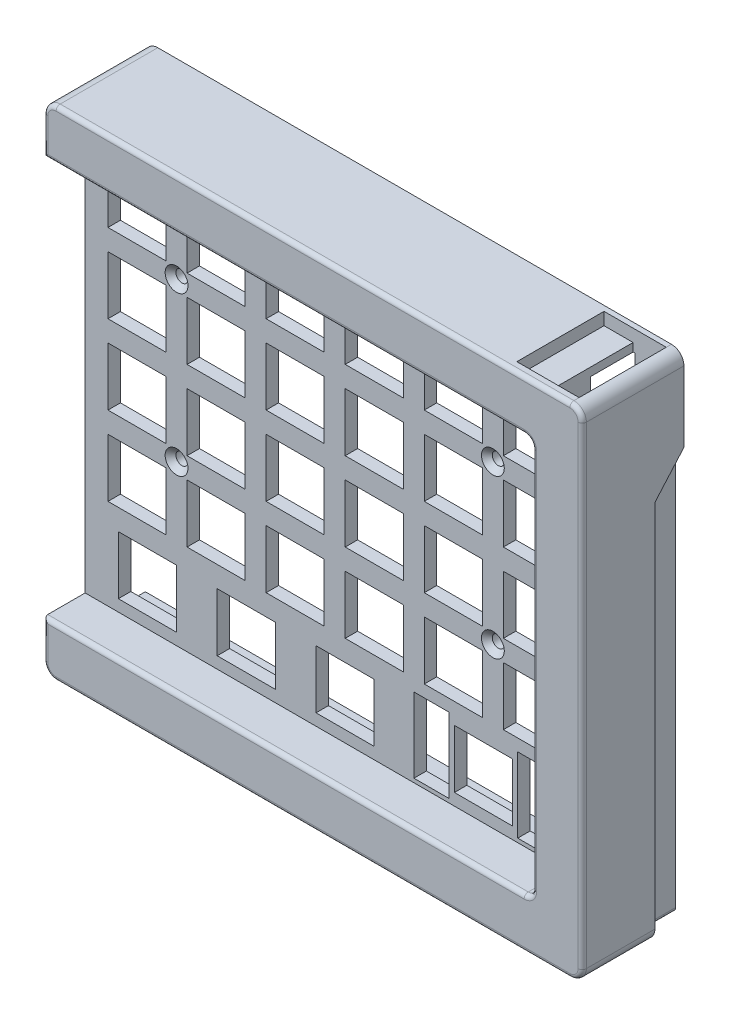
SolidWorks part; units mm, degrees
ref_plane "Front Plane" through (0, 0, 0) normal (0, 0, 1) x (1, 0, 0)
ref_plane "Top Plane" through (0, 0, 0) normal (0, 1, 0) x (1, 0, 0)
ref_plane "Right Plane" through (0, 0, 0) normal (1, 0, 0) x (0, 0, -1)
sketch "Sketch1" plane through (0, 0, 0) normal (0, 0, 1) x (1, 0, 0)
  line L1 (-61.875, -60) -> (61.875, -60)
  line L2 (-64.875, -57) -> (-64.875, 57)
  line L3 (-61.875, 60) -> (61.875, 60)
  line L4 (64.875, -57) -> (64.875, 57)
  line L5 (-64.875, -60) -> (64.875, 60) construction
  line L6 (-64.875, 60) -> (64.875, -60) construction
  arc A0 (61.875, -60) -> (64.875, -57) centre (61.875, -57) ccw
  arc A1 (61.875, 60) -> (64.875, 57) centre (61.875, 57) cw
  arc A2 (-64.875, 57) -> (-61.875, 60) centre (-61.875, 57) cw
  arc A3 (-61.875, -60) -> (-64.875, -57) centre (-61.875, -57) cw
  point P0 (0, 0)
  dimension "D3" = 3
  dimension "D1" = 129.75
  dimension "D2" = 120
extrude "Main Extrusion" add sketch "Sketch1" along normal blind 24.5
sketch "Sketch3" plane through (0, 0, 24.5) normal (0, 0, 1) x (1, 0, 0)
  line L0 (-64.875, 57) -> (-64.875, -57) construction
  line L1 (-64.875, 48) -> (50.875, 48)
  line L2 (-64.875, 48) -> (-64.875, -48)
  line L3 (-64.875, -48) -> (50.875, -48)
  line L4 (52.875, 46) -> (52.875, -46)
  line L5 (-64.875, 48) -> (52.875, -48) construction
  line L6 (-64.875, -48) -> (52.875, 48) construction
  line L7 (-61.875, -60) -> (61.875, -60) construction
  line L9 (61.875, 60) -> (-61.875, 60) construction
  line L11 (64.875, -57) -> (64.875, 57) construction
  arc A0 (50.875, 48) -> (52.875, 46) centre (50.875, 46) cw
  arc A1 (50.875, -48) -> (52.875, -46) centre (50.875, -46) ccw
  point P0 (-6, 0)
  dimension "D5" = 2
  dimension "D1" = 0
  dimension "D2" = 12
  dimension "D3" = 12
  dimension "D4" = 12
extrude "Front Cave" cut sketch "Sketch3" against normal blind 10
sketch "Sketch2" plane through (0, 0, 14.5) normal (0, 0, 1) x (1, 0, 0)
  line L0 (-59.375, -7.1) -> (-59.375, 6.9)
  line L1 (-59.375, 31) -> (-45.375, 31)
  line L2 (-59.375, 31) -> (-59.375, 45)
  line L3 (-59.375, 45) -> (-45.375, 45)
  line L4 (-45.375, 31) -> (-45.375, 45)
  line L5 (-59.375, 31) -> (-45.375, 45) construction
  line L6 (-59.375, 45) -> (-45.375, 31) construction
  line L7 (-40.325, 31) -> (-40.325, 45)
  line L8 (-40.325, 31) -> (-26.325, 31)
  line L9 (-26.325, 31) -> (-26.325, 45)
  line L10 (-40.325, 45) -> (-26.325, 45)
  line L11 (-21.275, 31) -> (-21.275, 45)
  line L12 (-21.275, 31) -> (-7.275, 31)
  line L13 (-7.275, 31) -> (-7.275, 45)
  line L14 (-21.275, 45) -> (-7.275, 45)
  line L15 (-2.225, 31) -> (-2.225, 45)
  line L16 (-2.225, 31) -> (11.775, 31)
  line L17 (11.775, 31) -> (11.775, 45)
  line L18 (-2.225, 45) -> (11.775, 45)
  line L19 (16.825, 31) -> (16.825, 45)
  line L20 (16.825, 31) -> (30.825, 31)
  line L21 (30.825, 31) -> (30.825, 45)
  line L22 (16.825, 45) -> (30.825, 45)
  line L23 (35.875, 31) -> (35.875, 45)
  line L24 (35.875, 31) -> (49.875, 31)
  line L25 (49.875, 31) -> (49.875, 45)
  line L26 (35.875, 45) -> (49.875, 45)
  line L27 (31.084, -31.15) -> (31.084, -45.15) construction
  line L28 (22.8344, -29.05) -> (14.3344, -29.05)
  line L29 (-59.375, 6.9) -> (-45.375, 6.9)
  line L30 (-59.375, 11.95) -> (-59.375, 25.95)
  line L31 (-59.375, 11.95) -> (-45.375, 11.95)
  line L32 (-45.375, 11.95) -> (-45.375, 25.95)
  line L33 (-59.375, 25.95) -> (-45.375, 25.95)
  line L34 (-40.325, 11.95) -> (-40.325, 25.95)
  line L35 (-40.325, 25.95) -> (-26.325, 25.95)
  line L36 (-26.325, 11.95) -> (-26.325, 25.95)
  line L37 (-40.325, 11.95) -> (-26.325, 11.95)
  line L38 (-21.275, 11.95) -> (-21.275, 25.95)
  line L39 (-21.275, 25.95) -> (-7.275, 25.95)
  line L40 (-7.275, 11.95) -> (-7.275, 25.95)
  line L41 (-21.275, 11.95) -> (-7.275, 11.95)
  line L42 (-2.225, 11.95) -> (-2.225, 25.95)
  line L43 (-2.225, 25.95) -> (11.775, 25.95)
  line L44 (11.775, 11.95) -> (11.775, 25.95)
  line L45 (-2.225, 11.95) -> (11.775, 11.95)
  line L46 (16.825, 11.95) -> (16.825, 25.95)
  line L47 (16.825, 25.95) -> (30.825, 25.95)
  line L48 (30.825, 11.95) -> (30.825, 25.95)
  line L49 (16.825, 11.95) -> (30.825, 11.95)
  line L50 (35.875, 11.95) -> (35.875, 25.95)
  line L51 (35.875, 25.95) -> (49.875, 25.95)
  line L52 (49.875, 11.95) -> (49.875, 25.95)
  line L53 (35.875, 11.95) -> (49.875, 11.95)
  line L54 (-45.375, -7.1) -> (-45.375, 6.9)
  line L55 (-59.375, -7.1) -> (-45.375, -7.1)
  line L56 (-40.325, -7.1) -> (-40.325, 6.9)
  line L57 (-40.325, 6.9) -> (-26.325, 6.9)
  line L58 (-26.325, -7.1) -> (-26.325, 6.9)
  line L59 (-40.325, -7.1) -> (-26.325, -7.1)
  line L60 (-21.275, -7.1) -> (-21.275, 6.9)
  line L61 (-21.275, 6.9) -> (-7.275, 6.9)
  line L62 (-7.275, -7.1) -> (-7.275, 6.9)
  line L63 (-21.275, -7.1) -> (-7.275, -7.1)
  line L64 (-2.225, -7.1) -> (-2.225, 6.9)
  line L65 (-2.225, 6.9) -> (11.775, 6.9)
  line L66 (11.775, -7.1) -> (11.775, 6.9)
  line L67 (-2.225, -7.1) -> (11.775, -7.1)
  line L68 (16.825, -7.1) -> (16.825, 6.9)
  line L69 (16.825, 6.9) -> (30.825, 6.9)
  line L70 (30.825, -7.1) -> (30.825, 6.9)
  line L71 (16.825, -7.1) -> (30.825, -7.1)
  line L72 (35.875, -7.1) -> (35.875, 6.9)
  line L73 (35.875, 6.9) -> (49.875, 6.9)
  line L74 (49.875, -7.1) -> (49.875, 6.9)
  line L75 (35.875, -7.1) -> (49.875, -7.1)
  line L76 (-59.375, -26.15) -> (-59.375, -12.15)
  line L77 (-59.375, -12.15) -> (-45.375, -12.15)
  line L78 (-45.375, -26.15) -> (-45.375, -12.15)
  line L79 (-59.375, -26.15) -> (-45.375, -26.15)
  line L80 (-40.325, -26.15) -> (-40.325, -12.15)
  line L81 (-40.325, -12.15) -> (-26.325, -12.15)
  line L82 (-26.325, -26.15) -> (-26.325, -12.15)
  line L83 (-40.325, -26.15) -> (-26.325, -26.15)
  line L84 (-21.275, -26.15) -> (-21.275, -12.15)
  line L85 (-21.275, -12.15) -> (-7.275, -12.15)
  line L86 (-7.275, -26.15) -> (-7.275, -12.15)
  line L87 (-21.275, -26.15) -> (-7.275, -26.15)
  line L88 (-2.225, -26.15) -> (-2.225, -12.15)
  line L89 (-2.225, -12.15) -> (11.775, -12.15)
  line L90 (11.775, -26.15) -> (11.775, -12.15)
  line L91 (-2.225, -26.15) -> (11.775, -26.15)
  line L92 (16.825, -26.15) -> (16.825, -12.15)
  line L93 (16.825, -12.15) -> (30.825, -12.15)
  line L94 (30.825, -26.15) -> (30.825, -12.15)
  line L95 (16.825, -26.15) -> (30.825, -26.15)
  line L96 (35.875, -26.15) -> (35.875, -12.15)
  line L97 (35.875, -12.15) -> (49.875, -12.15)
  line L98 (49.875, -26.15) -> (49.875, -12.15)
  line L99 (35.875, -26.15) -> (49.875, -26.15)
  line L100 (-33.063, -31.2) -> (-33.063, -45.2)
  line L101 (-56.875, -31.2) -> (-42.875, -31.2)
  line L102 (-56.875, -31.2) -> (-56.875, -45.2)
  line L103 (-56.875, -45.2) -> (-42.875, -45.2)
  line L104 (-42.875, -31.2) -> (-42.875, -45.2)
  line L105 (-56.875, -31.2) -> (-42.875, -45.2) construction
  line L106 (-56.875, -45.2) -> (-42.875, -31.2) construction
  line L107 (-33.063, -31.2) -> (-19.063, -31.2)
  line L108 (-19.063, -31.2) -> (-19.063, -45.2)
  line L109 (-33.063, -45.2) -> (-19.063, -45.2)
  line L110 (-9.251, -31.2) -> (-9.251, -45.2)
  line L111 (-9.251, -31.2) -> (4.749, -31.2)
  line L112 (4.749, -31.2) -> (4.749, -45.2)
  line L113 (-9.251, -45.2) -> (4.749, -45.2)
  line L114 (-61.875, -60) -> (61.875, -60) construction
  line L115 (24.084, -31.15) -> (38.084, -31.15)
  line L116 (24.084, -31.15) -> (24.084, -45.15)
  line L117 (24.084, -45.15) -> (38.084, -45.15)
  line L118 (38.084, -31.15) -> (38.084, -45.15)
  line L119 (24.084, -31.15) -> (38.084, -45.15) construction
  line L120 (24.084, -45.15) -> (38.084, -31.15) construction
  line L125 (61.875, 60) -> (-61.875, 60) construction
  line L126 (-64.875, 57) -> (-64.875, 48) construction
  line L127 (14.3344, -47.05) -> (14.3344, -29.05)
  line L132 (22.8344, -47.05) -> (14.3344, -47.05)
  line L133 (22.8344, -47.05) -> (22.8344, -29.05)
  line L134 (39.3336, -47.05) -> (47.8336, -47.05)
  line L135 (39.3336, -47.05) -> (39.3336, -29.05)
  line L136 (39.3336, -29.05) -> (47.8336, -29.05)
  line L137 (47.8336, -47.05) -> (47.8336, -29.05)
  line L138 (39.3336, -47.05) -> (47.8336, -29.05) construction
  line L139 (39.3336, -29.05) -> (47.8336, -47.05) construction
  point P0 (-52.375, 38)
  point P29 (-49.875, -38.2)
  point P107 (31.084, -38.15)
  point P136 (18.584, -37.55)
  point P141 (43.5836, -38.05)
  dimension "D1" = 14
  dimension "D2" = 14
  dimension "D3" = 6
  dimension "D5" = 15
  dimension "D6" = 5.05
  dimension "D7" = 2
  dimension "D8" = 5.05
  dimension "D10" = 5.05
  dimension "D11" = 14
  dimension "D12" = 14
  dimension "D13" = 5.5
  dimension "D14" = 5.05
  dimension "D16" = 9.812
  dimension "D17" = 14
  dimension "D18" = 14
  dimension "D19" = 19.335
  dimension "D20" = 5
  dimension "D21" = 8
  dimension "D44" = 8.5
  dimension "D45" = 18
  dimension "D46" = 12.5
  dimension "D47" = 12.95
  dimension "D9" = 3
  dimension "D15" = 3
extrude "Key Cutouts" cut sketch "Sketch2" against normal blind 3
sketch "Sketch4" plane through (0, 0, 0) normal (0, 0, 1) x (1, 0, 0)
  line L0 (61.875, 60) -> (-61.875, 60) construction
  line L1 (-64.875, 55) -> (54.375, 55)
  line L2 (-64.875, 55) -> (-64.875, -55)
  line L3 (-64.875, -55) -> (59.875, -55)
  line L4 (59.875, 17.5) -> (59.875, -55)
  line L5 (-64.875, 55) -> (59.875, -55) construction
  line L7 (-61.875, -60) -> (61.875, -60) construction
  line L8 (64.875, -57) -> (64.875, 57) construction
  line L12 (59.875, 17.5) -> (54.375, 17.5)
  line L13 (54.375, 55) -> (54.375, 17.5)
  line L14 (-64.875, 57) -> (-64.875, -57) construction
  point P0 (0.3939, -2.5517)
  dimension "D1" = 5
  dimension "D2" = 5
  dimension "D3" = 5
  dimension "D4" = 5.5
  dimension "D5" = 37.5
extrude "Cut-Extrude1" cut sketch "Sketch4" along normal up to surface (11.5 mm away) contours L2 L3 L4 L12 L13 L1 up to face at (-52.375, 18.95, 11.5)
hole_wizard "CSK for M2.5 Countersunk Flat Head Screw1" positions "3DSketch1" profile "Sketch5" countersink size "M2.5" standard "ISO" end condition through all
sketch3d "3DSketch1"
  line L0 (-45.375, -7.1, 14.5) -> (-45.375, 6.9, 14.5) construction
  line L1 (-26.325, -12.15, 14.5) -> (-40.325, -12.15, 14.5) construction
  line L2 (-59.375, 31, 14.5) -> (-45.375, 31, 14.5) construction
  line L4 (-40.325, 25.95, 14.5) -> (-40.325, 11.95, 14.5) construction
  line L5 (30.825, 11.95, 14.5) -> (30.825, 25.95, 14.5) construction
  line L6 (49.875, 25.95, 14.5) -> (35.875, 25.95, 14.5) construction
  line L7 (35.875, -12.15, 14.5) -> (35.875, -26.15, 14.5) construction
  line L8 (35.875, -7.1, 14.5) -> (49.875, -7.1, 14.5) construction
  point P0 (-42.85, 28.475, 14.5)
  point P2 (33.35, 28.475, 14.5)
  point P4 (33.35, -9.625, 14.5)
  point P6 (-42.85, -9.625, 14.5)
  dimension "D1" = 2.525
  dimension "D2" = 2.525
  dimension "D3" = 2.525
  dimension "D4" = 2.525
  dimension "D5" = 2.525
  dimension "D6" = 2.525
  dimension "D7" = 2.525
  dimension "D8" = 2.525
sketch "Sketch5" plane through (-42.85, 28.475, 14.5) normal (1, 0, 0) x (0, -1, 0)
  line L0 (0, 0) -> (0, 14.5)
  line L1 (0, 14.5) -> (1.45, 14.5)
  line L2 (1.45, 14.5) -> (1.45, 1.3)
  line L3 (1.45, 1.3) -> (2.75, 0)
  line L5 (2.75, 0) -> (0, 0)
  line L6 (-1.45, 1.3) -> (-2.75, 0) construction
  line L11 (0, -6.35) -> (0, 107.95) construction
  dimension "Thru Hole Dia." = 2.9
  dimension "Thru Hole Depth" = 14.5
  dimension "Near C'Sink Dia." = 5.5
  dimension "Near C'Sink Angle" = 90
sketch "Sketch6" plane through (0, -60, 0) normal (0, -1, 0) x (1, 0, 0)
  line L0 (-44.875, 0) -> (-36.875, 7)
  line L1 (-61.875, 0) -> (61.875, 0) construction
  line L2 (-36.875, 7) -> (64.875, 7)
  line L3 (64.875, 7) -> (64.875, 0)
  line L4 (64.875, 0) -> (-44.875, 0)
  line L5 (-61.875, 24.5) -> (-61.875, 0) construction
  line L7 (64.875, 24.5) -> (64.875, 0) construction
  dimension "D1" = 25
  dimension "D2" = 17
  dimension "D5" = 7
extrude "Cut-Extrude2" cut sketch "Sketch6" against normal blind 2
sketch "Sketch8" plane through (64.875, 0, 0) normal (1, 0, 0) x (0, 0, -1)
  line L0 (0, -60) -> (-7, -60)
  line L1 (0, -57) -> (0, 57) construction
  line L2 (-7, -60) -> (-7, 32)
  line L3 (-7, 32) -> (0, 40)
  line L4 (0, 40) -> (0, -60)
  line L6 (-24.5, -60) -> (-7, -60) construction
  line L7 (-24.5, 57) -> (0, 57) construction
  dimension "D3" = 17
  dimension "D4" = 25
  dimension "D5" = 7
extrude "Cut-Extrude3" cut sketch "Sketch8" against normal blind 2
fillet "Fillet1" radius 1 15 edges at (-64.875, 52.5, 24.5) (-63.9963, 59.1213, 24.5) (0, 60, 24.5) (63.9963, 59.1213, 24.5) (64.875, 0, 24.5) (63.9963, -59.1213, 24.5) (0, -60, 24.5) (-63.9963, -59.1213, 24.5) (-64.875, -52.5, 24.5) (-7, -48, 24.5) (52.2892, -47.4142, 24.5) (52.875, 0, 24.5) (52.2892, 47.4142, 24.5) (-7, 48, 24.5) (62.875, -58, 3.5)
sketch "Sketch9" plane through (0, 60, 0) normal (0, 1, 0) x (1, 0, 0)
  line L0 (61.875, -23.5) -> (61.875, 0) construction
  line L1 (61.875, -1.25) -> (53.875, -1.25)
  line L2 (61.875, -1.25) -> (61.875, -22.25)
  line L3 (61.875, -22.25) -> (53.875, -22.25)
  line L4 (53.875, -1.25) -> (53.875, -22.25)
  line L5 (-61.875, -11.75) -> (61.875, -11.75) construction
  line L6 (-61.875, -23.5) -> (-61.875, 0) construction
  point P10 (53.875, -11.75)
  dimension "D1" = 8
  dimension "D2" = 21
extrude "Cut-Extrude4" cut sketch "Sketch9" against normal blind 41
sketch "Sketch10" plane through (0, 0, 11.5) normal (0, 0, -1) x (-1, 0, 0)
  line L0 (-59.875, 17.5) -> (-54.375, 17.5) construction
  line L1 (-59.875, 17.5) -> (-53.875, 17.5)
  line L2 (-59.875, 17.5) -> (-59.875, 7.5)
  line L3 (-59.875, 7.5) -> (-53.875, 7.5)
  line L4 (-53.875, 17.5) -> (-53.875, 7.5)
  line L5 (-53.875, 55) -> (-53.875, 19) construction
  line L6 (-59.875, 17.5) -> (-59.875, -55) construction
  dimension "D1" = 10
extrude "Cut-Extrude5" cut sketch "Sketch10" against normal up to surface (10.75 mm away) up to face at (57.875, 39.5, 22.25)
sketch "Sketch11" plane through (0, 19, 0) normal (0, 1, 0) x (1, 0, 0)
  line L0 (57.875, -6.25) -> (57.875, -17.25) construction
  line L1 (59.875, -6.25) -> (59.875, -17.25)
  line L2 (55.875, -6.25) -> (55.875, -17.25)
  line L3 (53.875, -1.25) -> (53.875, -22.25) construction
  line L6 (61.875, -1.25) -> (53.875, -1.25) construction
  arc A0 (59.875, -6.25) -> (55.875, -6.25) centre (57.875, -6.25) ccw
  arc A1 (55.875, -17.25) -> (59.875, -17.25) centre (57.875, -17.25) ccw
  point P2 (57.875, -11.75)
  dimension "D1" = 2
  dimension "D2" = 11
  dimension "D3" = 4
  dimension "D4" = 10.5
extrude "Cut-Extrude6" cut sketch "Sketch11" against normal up to surface (1.5 mm away) up to face at (56.0417, 17.5, 11.25)
sketch "Sketch13" plane through (0, 0, 11.5) normal (0, 0, -1) x (-1, 0, 0)
  line L0 (-59.875, 7.5) -> (-59.875, -55) construction
  line L1 (-59.875, 5) -> (-56.675, 5)
  line L2 (-59.875, 5) -> (-59.875, -55)
  line L3 (-59.875, -55) -> (-56.675, -55)
  line L4 (-56.675, 5) -> (-56.675, -55)
  line L5 (64.875, -55) -> (-59.875, -55) construction
  dimension "D1" = 3.2
  dimension "D2" = 60
extrude "Cut-Extrude8" cut sketch "Sketch13" against normal blind 7
sketch "Sketch15" plane through (0, 60, 0) normal (0, 1, 0) x (1, 0, 0)
  line L0 (53.875, -22.25) -> (61.875, -22.25) construction
  line L1 (53.875, -1.25) -> (46.875, -1.25)
  line L2 (53.875, -1.25) -> (53.875, -22.25)
  line L3 (53.875, -22.25) -> (46.875, -22.25)
  line L4 (46.875, -1.25) -> (46.875, -22.25)
  dimension "D1" = 7
extrude "Cut-Extrude9" cut sketch "Sketch15" against normal blind 3
